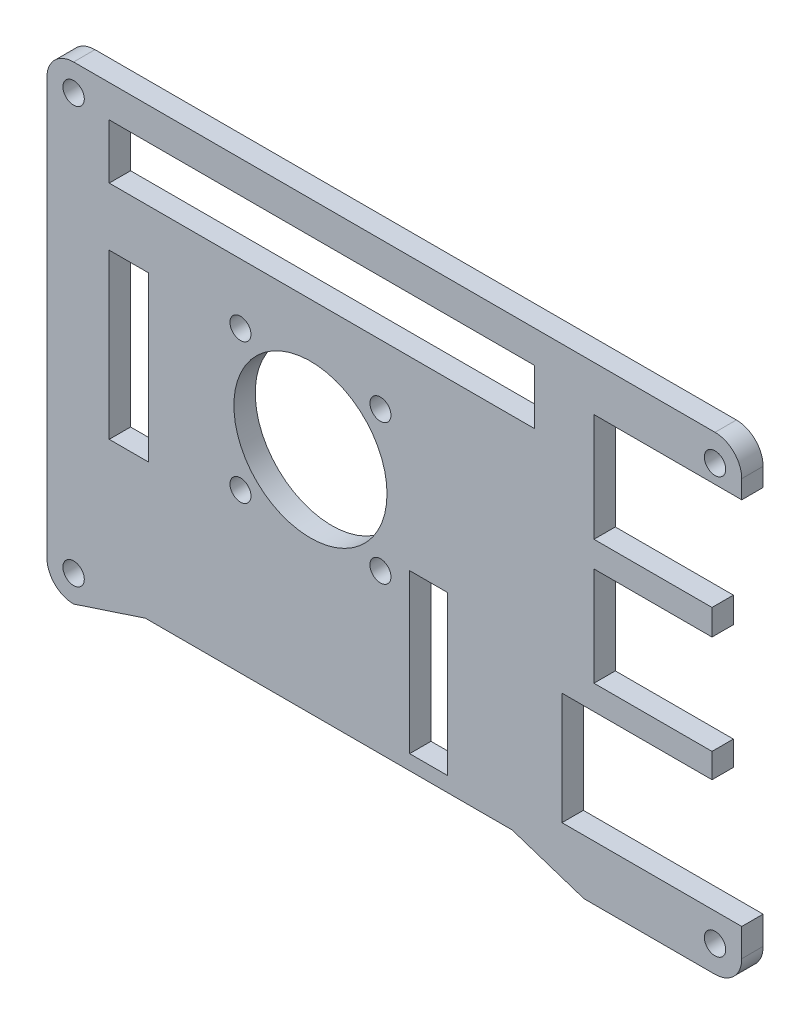
SolidWorks part; units mm, degrees
ref_plane "Front Plane" through (0, 0, 0) normal (0, 0, 1) x (1, 0, 0)
ref_plane "Top Plane" through (0, 0, 0) normal (0, 1, 0) x (1, 0, 0)
ref_plane "Right Plane" through (0, 0, 0) normal (1, 0, 0) x (0, 0, -1)
sketch "Sketch1" plane through (0, 0, 0) normal (0, 0, 1) x (1, 0, 0)
  line L1 (61.2149, 24.0683) -> (61.2149, 26.6839) construction
  line L2 (57.4049, 30.5077) -> (-34.0849, 30.5077) construction
  line L5 (56.975, 4.9979) -> (56.975, 8.6582) construction
  line L9 (56.975, -12.628) -> (56.975, -9.1218) construction
  line L10 (35.575, -12.628) -> (56.975, -12.628) construction
  line L11 (35.575, -28.6278) -> (35.575, -12.628) construction
  line L12 (61.2149, -28.6278) -> (35.575, -28.6278) construction
  line L13 (61.2149, -32.6134) -> (61.2149, -28.6278) construction
  line L14 (38.7143, -36.451) -> (57.405, -36.451) construction
  line L15 (28.4743, -33.0844) -> (38.7143, -36.451) construction
  line L16 (-23.8449, -33.0844) -> (28.4743, -33.0844) construction
  line L17 (-34.0849, -36.451) -> (-23.8449, -33.0844) construction
  line L18 (-37.8949, 26.6977) -> (-37.8949, -32.641) construction
  line L19 (61.2149, 24.0683) -> (40.1348, 24.0683)
  line L20 (61.2149, 24.0683) -> (61.2149, 26.6839)
  line L21 (57.4049, 30.5077) -> (-34.0849, 30.5077)
  line L22 (40.1348, 24.0683) -> (40.1348, 8.6582)
  line L23 (40.1348, 8.6582) -> (56.975, 8.6582)
  line L24 (56.975, 4.9979) -> (56.975, 8.6582)
  line L25 (56.975, 4.9979) -> (40.1348, 4.9979)
  line L26 (40.1348, 4.9979) -> (40.1348, -9.1218)
  line L27 (40.1348, -9.1218) -> (56.975, -9.1218)
  line L28 (56.975, -12.628) -> (56.975, -9.1218)
  line L29 (35.575, -12.628) -> (56.975, -12.628)
  line L30 (35.575, -28.6278) -> (35.575, -12.628)
  line L31 (61.2149, -28.6278) -> (35.575, -28.6278)
  line L32 (61.2149, -32.6134) -> (61.2149, -28.6278)
  line L33 (38.7143, -36.451) -> (57.405, -36.451)
  line L34 (28.4743, -33.0844) -> (38.7143, -36.451)
  line L35 (-23.8449, -33.0844) -> (28.4743, -33.0844)
  line L36 (-34.0849, -36.451) -> (-23.8449, -33.0844)
  line L37 (-37.8949, 26.6977) -> (-37.8949, -32.641)
  line L38 (-23.4169, -23.6989) -> (-23.4169, 9.8012) construction
  line L39 (-29.0049, 25.897) -> (31.6883, 25.897)
  line L40 (-29.0049, 25.897) -> (-29.0049, 18.087)
  line L41 (-29.0049, 18.087) -> (31.6883, 18.087)
  line L42 (31.6883, 25.897) -> (31.6883, 18.087)
  line L43 (-29.0049, 9.8012) -> (-23.4169, 9.8012)
  line L44 (-29.0049, 9.8012) -> (-29.0049, -13.5668)
  line L45 (-29.0049, -13.5668) -> (-23.4169, -13.5668)
  line L46 (-23.4169, 9.8012) -> (-23.4169, -13.5668)
  line L47 (-29.0049, 9.2932) -> (-23.4169, 9.2932)
  line L50 (13.845, -8.3602) -> (19.2484, -8.3602)
  line L51 (13.845, -8.3602) -> (13.845, -30.9668)
  line L52 (13.845, -30.9668) -> (19.2484, -30.9668)
  line L53 (19.2484, -8.3602) -> (19.2484, -30.9668)
  arc A0 (61.2149, 26.6839) -> (57.4049, 30.5077) centre (57.4049, 26.6977) ccw construction
  arc A2 (57.405, -36.451) -> (61.2149, -32.6134) centre (57.405, -32.641) ccw construction
  arc A3 (-37.8949, -32.641) -> (-34.0849, -36.451) centre (-34.0849, -32.641) ccw construction
  arc A4 (-34.0849, 30.5077) -> (-37.8949, 26.6977) centre (-34.0849, 26.6977) ccw construction
  arc A7 (61.2149, 26.6839) -> (57.4049, 30.5077) centre (57.4049, 26.6977) ccw
  circle A8 centre (57.405, -32.641) radius 1.524
  arc A9 (57.405, -36.451) -> (61.2149, -32.6134) centre (57.405, -32.641) ccw
  arc A10 (-37.8949, -32.641) -> (-34.0849, -36.451) centre (-34.0849, -32.641) ccw
  arc A11 (-34.0849, 30.5077) -> (-37.8949, 26.6977) centre (-34.0849, 26.6977) ccw
  circle A12 centre (-34.0849, -32.641) radius 1.524
  circle A13 centre (-34.0849, 26.6977) radius 1.524
  circle A15 centre (57.4049, 26.6977) radius 1.524
  dimension "D5" = 3.048
  dimension "D1" = 23.368
  dimension "D2" = 0.508
  dimension "D3" = 16.8402
  dimension "D4" = 16.8402
extrude "Boss-Extrude1" add sketch "Sketch1" along normal blind 3.048
sketch "Sketch2" plane through (0, 0, 3.048) normal (0, 0, 1) x (1, 0, 0)
  line L2 (-37.8949, 26.6977) -> (-37.8949, -32.641) construction
  line L5 (57.4049, 30.5077) -> (-34.0849, 30.5077) construction
  line L6 (-10.2851, -8.9639) -> (-10.2851, 8.0033) construction
  line L7 (-8.7865, -10.4625) -> (8.1807, -10.4625) construction
  line L8 (9.6793, -8.9639) -> (9.6793, 8.0033) construction
  line L9 (8.1807, 9.5019) -> (-8.7865, 9.5019) construction
  line L10 (-10.2851, -10.4625) -> (9.6793, 9.5019) construction
  circle A0 centre (-0.3029, -0.4803) radius 10.922
  circle A1 centre (-10.2851, -10.4625) radius 1.4986
  circle A2 centre (-10.2851, 9.5019) radius 1.4986
  circle A3 centre (9.6793, -10.4625) radius 1.4986
  circle A4 centre (9.6793, 9.5019) radius 1.4986
  dimension "D1" = 26.67
  dimension "D2" = 20.066
  dimension "D3" = 21.844
  dimension "D4" = 16.9672
  dimension "D5" = 2.9972
extrude "Cut-Extrude1" cut sketch "Sketch2" against normal through all
sketch "Sketch3" [suppressed] plane through (0, 0, 3.048) normal (0, 0, 1) x (1, 0, 0)
  line L0 (13.845, -30.9668) -> (19.2484, -30.9668) construction
  line L1 (-29.0049, 25.897) -> (31.6883, 25.897)
  line L2 (-29.0049, 25.897) -> (-29.0049, -30.9668)
  line L3 (-29.0049, -30.9668) -> (31.6883, -30.9668)
  line L4 (31.6883, 25.897) -> (31.6883, -30.9668)
  line L5 (31.6883, 25.897) -> (31.6883, 18.087) construction
extrude "Boss-Extrude2" [suppressed] add sketch "Sketch3" against normal up to vertex
sketch "Sketch4" plane through (0, 0, 3.048) normal (0, 0, 1) x (1, 0, 0)
  circle A0 centre (-34.0849, -32.641) radius 1.524
  circle A1 centre (57.405, -32.641) radius 1.524
  circle A2 centre (-34.0849, -32.641) radius 1.524
  circle A3 centre (-34.0849, 26.6977) radius 1.524
  circle A4 centre (57.4049, 26.6977) radius 1.524
  dimension "D1" = 3.048
extrude "Cut-Extrude2" [suppressed] cut sketch "Sketch4" against normal through all
